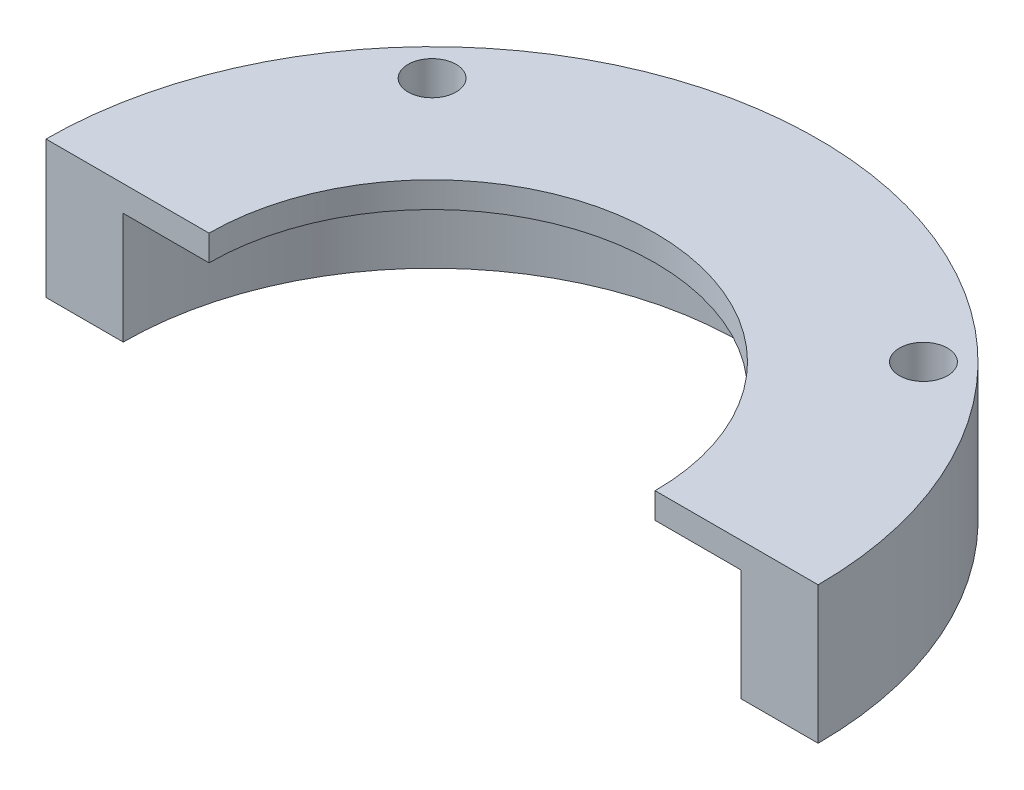
SolidWorks part; units mm, degrees
material "6061-T6 (SS)"
ref_plane "Front Plane" through (0, 0, 0) normal (0, 0, 1) x (1, 0, 0)
ref_plane "Top Plane" through (0, 0, 0) normal (0, 1, 0) x (1, 0, 0)
ref_plane "Right Plane" through (0, 0, 0) normal (1, 0, 0) x (0, 0, -1)
sketch "Sketch1" plane through (0, 0, 0) normal (0, 1, 0) x (1, 0, 0)
  circle A0 centre (0, 0) radius 28.575
  dimension "D1" = 57.15
extrude "Boss-Extrude1" add sketch "Sketch1" along normal blind 10.16 contours A0
sketch "Sketch2" plane through (0, 0, 0) normal (0, -1, 0) x (1, 0, 0)
  circle A0 centre (0, 0) radius 16.51
  dimension "D1" = 33.02
extrude "Cut-Extrude1" cut sketch "Sketch2" against normal through all
sketch "Sketch3" plane through (0, 0, 0) normal (0, -1, 0) x (1, 0, 0)
  circle A0 centre (0, 0) radius 22.86
  dimension "D1" = 45.72
extrude "Cut-Extrude2" cut sketch "Sketch3" against normal blind 8.255
sketch "Sketch4" plane through (0, 10.16, 0) normal (0, 1, 0) x (1, 0, 0)
  line L1 (-39.5745, 0) -> (49.3406, 0)
  line L2 (-39.5745, 0) -> (-39.5745, -51.3525)
  line L3 (-39.5745, -51.3525) -> (49.3406, -51.3525)
  line L4 (49.3406, 0) -> (49.3406, -51.3525)
extrude "Cut-Extrude3" cut sketch "Sketch4" against normal through all
sketch "Sketch6" plane through (0, 0, 0) normal (0, -1, 0) x (1, 0, 0)
  line L0 (0, 0) -> (0, -44.8534) construction
  line L1 (0, 0) -> (18.185, -18.185) construction
  line L2 (0, 0) -> (-18.185, -18.185) construction
  circle A0 centre (0, 0) radius 25.7175 construction
  circle A1 centre (18.185, -18.185) radius 1.778
  circle A2 centre (-18.185, -18.185) radius 1.778
  dimension "D1" = 51.435
  dimension "D4" = 3.556
  dimension "D5" = 3.556
  dimension "D2" = 45
  dimension "D3" = 45
extrude "Cut-Extrude4" cut sketch "Sketch6" against normal up to next
equation "\"D5@Sketch6\"=\"D4@Sketch6\""
